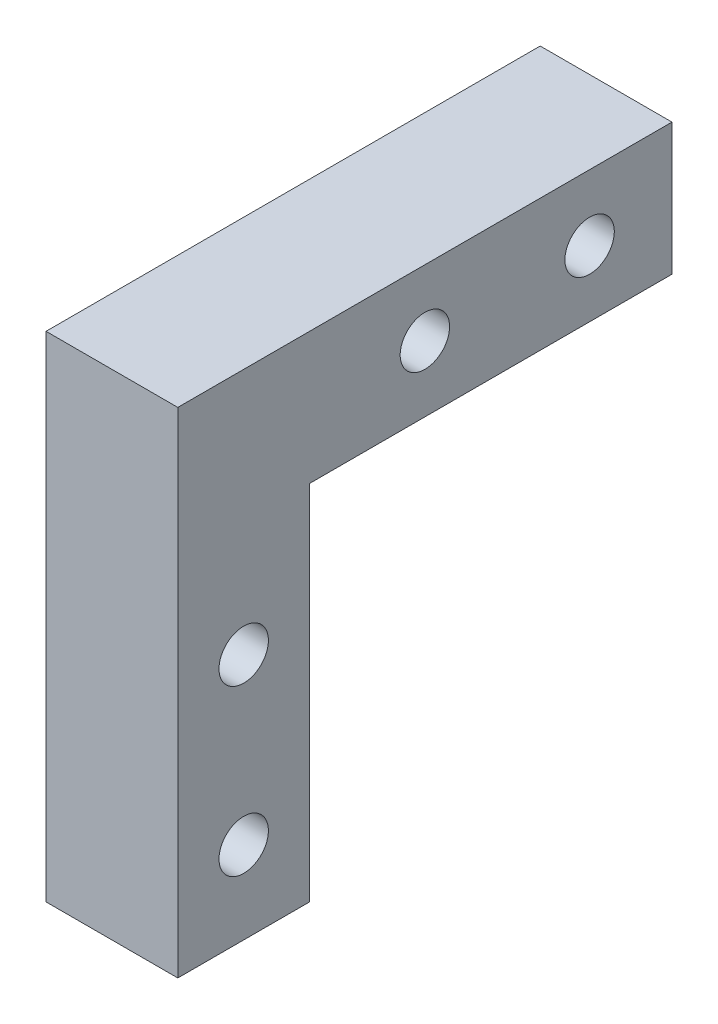
SolidWorks part; units mm, degrees
material "1060 Alloy"
ref_plane "Front Plane" through (0, 0, 0) normal (0, 0, 1) x (1, 0, 0)
ref_plane "Top Plane" through (0, 0, 0) normal (0, 1, 0) x (1, 0, 0)
ref_plane "Right Plane" through (0, 0, 0) normal (1, 0, 0) x (0, 0, -1)
sketch "Sketch1" plane through (0, 0, 0) normal (1, 0, 0) x (0, 0, -1)
  line L0 (0, 0) -> (0, -44)
  line L1 (0, -44) -> (-16, -44)
  line L2 (-16, -44) -> (-16, 16)
  line L3 (-16, 16) -> (44, 16)
  line L4 (44, 16) -> (44, 0)
  line L5 (44, 0) -> (0, 0)
  dimension "D1" = 16
  dimension "D2" = 16
  dimension "D3" = 60
  dimension "D4" = 60
extrude "Boss-Extrude1" add sketch "Sketch1" along normal mid plane 16
sketch "Sketch2" plane through (8, 0, 0) normal (1, 0, 0) x (0, 0, -1)
  line L0 (-8, -44) -> (-8, 18.3951) construction
  line L1 (-16, -44) -> (0, -44) construction
  line L2 (44, 8) -> (-21.6346, 8) construction
  line L3 (44, 0) -> (44, 16) construction
  circle A0 centre (-8, -34) radius 3
  circle A1 centre (-8, -14) radius 3
  circle A2 centre (14, 8) radius 3
  circle A3 centre (34, 8) radius 3
  dimension "D1" = 6
  dimension "D2" = 20
  dimension "D3" = 10
  dimension "D4" = 20
  dimension "D5" = 10
extrude "Cut-Extrude1" cut sketch "Sketch2" against normal through all
